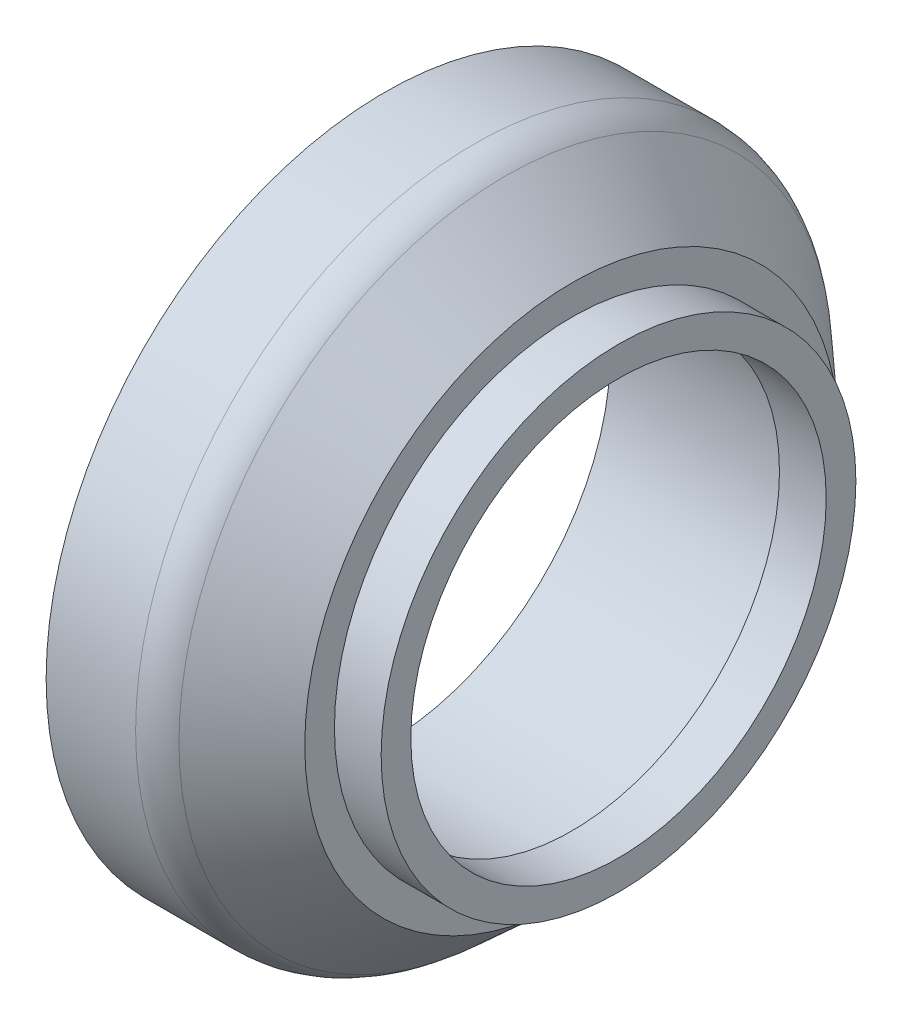
SolidWorks part; units mm, degrees
ref_plane "Płaszczyzna przednia" through (0, 0, 0) normal (0, 0, 1) x (1, 0, 0)
ref_plane "Płaszczyzna górna" through (0, 0, 0) normal (0, 1, 0) x (1, 0, 0)
ref_plane "Płaszczyzna prawa" through (0, 0, 0) normal (1, 0, 0) x (0, 0, -1)
sketch "Szkic1" plane through (0, 0, 0) normal (0, 0, 1) x (1, 0, 0)
  line L0 (0, 48.25) -> (0, 0) construction
  line L1 (0, 0) -> (38.4176, 0) construction
  line L2 (0, 48.25) -> (40, 48.25)
  line L3 (40, 48.25) -> (40, 57.15)
  line L4 (40, 57.15) -> (23, 72.5)
  line L5 (23, 72.5) -> (0, 72.5)
  line L6 (0, 72.5) -> (0, 48.25)
  dimension "D1" = 40
  dimension "D2" = 48.25
  dimension "D3" = 57.15
  dimension "D4" = 72.5
  dimension "D5" = 23
revolve "Obrót1" add sketch "Szkic1" angle 360 about L1
fillet "Zaokrąglenie1" radius 10 1 edges at (23, 0, 72.5)
sketch "Szkic2" plane through (40, 0, 0) normal (1, 0, 0) x (0, 0, -1)
  circle A0 centre (0, 0) radius 50.8
  circle A1 centre (0, 0) radius 44.45
  dimension "D1" = 101.6
  dimension "D2" = 88.9
extrude "Dodanie-wyciągnięcie1" add sketch "Szkic2" along normal blind 10
sketch "Szkic3" plane through (0, 0, 0) normal (-1, 0, 0) x (0, 0, 1)
  circle A0 centre (0, 0) radius 62.5 construction
  circle A1 centre (0, 62.5) radius 5.35
  dimension "D1" = 125
  dimension "D2" = 10.7
extrude "Wytnij-wyciągnięcie1" cut sketch "Szkic3" against normal blind 19.4
chamfer "Sfazowanie1" distance 1 angle 45 1 edges at (0, 62.5, 5.35)
pattern_circular "Szyk kołowy1" count 12 over 360 about axis through (0, 0, 0) along (1, 0, 0) of "Sfazowanie1", "Wytnij-wyciągnięcie1"
